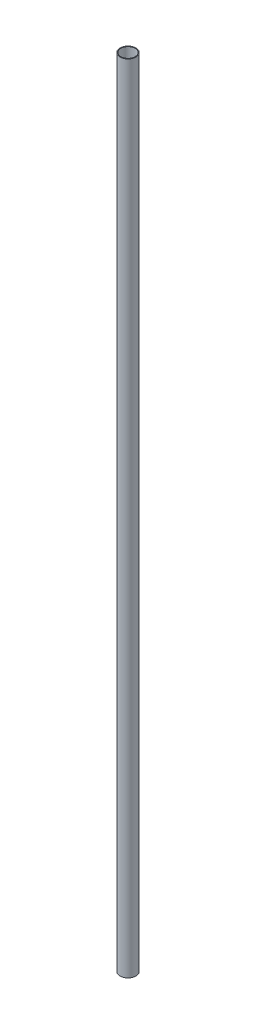
SolidWorks part; units mm, degrees
material "Thornel Mat VMA"
ref_plane "前视基准面" through (0, 0, 0) normal (0, 0, 1) x (1, 0, 0)
ref_plane "上视基准面" through (0, 0, 0) normal (0, 1, 0) x (1, 0, 0)
ref_plane "右视基准面" through (0, 0, 0) normal (1, 0, 0) x (0, 0, -1)
sketch "草图3" plane through (0, 0, 0) normal (0, 1, 0) x (1, 0, 0)
  circle A0 centre (0, 0) radius 10
  circle A1 centre (0, 0) radius 9
  dimension "D1" = 20
  dimension "D2" = 18
extrude "凸台-拉伸1" add sketch "草图3" along normal blind 1000
